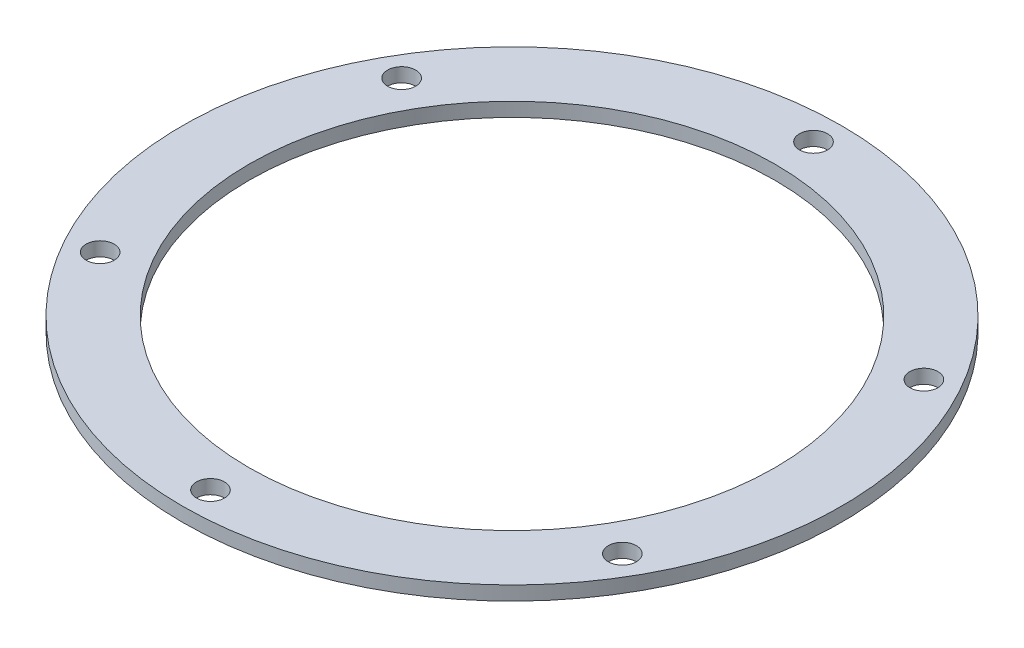
SolidWorks part; units mm, degrees
material "PLA"
ref_plane "Front Plane" through (0, 0, 0) normal (0, 0, 1) x (1, 0, 0)
ref_plane "Top Plane" through (0, 0, 0) normal (0, 1, 0) x (1, 0, 0)
ref_plane "Right Plane" through (0, 0, 0) normal (1, 0, 0) x (0, 0, -1)
sketch "Sketch1" plane through (0, 0, 0) normal (0, 1, 0) x (1, 0, 0)
  circle A0 centre (0, 0) radius 47
  circle A1 centre (0, 0) radius 37.5
  circle A2 centre (0, 0) radius 43 construction
  circle A3 centre (0, 43) radius 2
  circle A4 centre (37.2391, 21.5) radius 2
  circle A5 centre (37.2391, -21.5) radius 2
  circle A6 centre (0, -43) radius 2
  circle A7 centre (-37.2391, -21.5) radius 2
  circle A8 centre (-37.2391, 21.5) radius 2
  point P19 (0, 0)
  dimension "D1" = 94
  dimension "D2" = 75
  dimension "D3" = 86
  dimension "D4" = 4
  dimension "D5" = 6
extrude "Boss-Extrude1" add sketch "Sketch1" along normal blind 2
equation "\"Np_b\" = 39"
equation "\"Np_s\" = 33"
equation "\"Nr_b\" = 144"
equation "\"Nr_s\" = 138"
equation "\"Ns\" = 66"
equation "\"Motor_case_ID\" = 82.0"
equation "\"Motor_case_OD_base_to_chamfer\" = 5"
equation "\"Motor_case_OD_max\" = 96.5"
equation "\"Motor_case_thickness\" = 2.5"
equation "\"air_flow_hole_offset\" = 3"
equation "\"standard_bearing_insertion_chamfer\" = 0.5"
equation "\"alpha_p_b\" = 0.8539582918412414"
equation "\"alpha_p_s\" = 0.8539582918412449"
equation "\"alpha_r_b\" = 0.8539582918412343"
equation "\"alpha_r_s\" = 0.8539582918412485"
equation "\"alpha_s\" = 0.8539582918412449"
equation "\"base_plate_thickness\" = 4"
equation "\"bearing_ID\" = 60"
equation "\"bearing_OD\" = 78"
equation "\"bearing_height\" = 10"
equation "\"bearing mount thickness\" = 8"
equation "\"bearing_retainer_thickness\" = 2"
equation "\"beta_p_b\" = 2.907468031702132"
equation "\"beta_p_s\" = 3.7466288708629643"
equation "\"beta_r_b\" = 2.9579165836824686"
equation "\"beta_r_s\" = 3.0122644097694535"
equation "\"beta_s\" = 1.0193561435902372"
equation "\"carrier_PCD\" = 52.5"
equation "\"carrier_bearing_step_width\" = 1.5"
equation "\"carrier_small_ring_inner_bearing_ID\" = 20"
equation "\"carrier_small_ring_inner_bearing_OD\" = 32"
equation "\"carrier_small_ring_inner_bearing_flap\" = 2"
equation "\"carrier_small_ring_inner_bearing_height\" = 7"
equation "\"carrier_thickness\" = 4"
equation "\"carrier_trapezoidal_support_hole_PCD_offset_bearing_ID\" = 4"
equation "\"carrier_trapezoidal_support_hole_dia\" = 3"
equation "\"carrier_trapezoidal_support_hole_socket_head_dia\" = 5.5"
equation "\"carrier_trapezoidal_support_hole_wrench_size\" = 5.5"
equation "\"carrier_trapezoidal_support_sun_offset\" = 5"
equation "\"case_dist\" = 6.5"
equation "\"case_mounting_PCD\" = 89.0"
equation "\"case_mounting_bolt_depth\" = 4.5"
equation "\"case_mounting_hole_allen_socket_dia\" = 5.5"
equation "\"case_mounting_hole_dia\" = 3"
equation "\"case_mounting_hole_shift\" = 1.0"
equation "\"case_mounting_nut_clearance\" = 2"
equation "\"case_mounting_nut_thickness\" = 2.4"
equation "\"case_mounting_surface_height\" = 4"
equation "\"case_mounting_wrench_size\" = 5.5"
equation "\"central_hole_offset_from_motor_mount_PCD\" = 5"
equation "\"clearance_case_mount_holes_shell_thickness\" = 1"
equation "\"clearance_motor_and_case\" = 5.0"
equation "\"clearance_planet\" = 1.5"
equation "\"clearance_sun_coupler_sec_carrier\" = 1.5"
equation "\"clr_tip_root\" = 0.125"
equation "\"clr_tip_root_s\" = 0.125"
equation "\"db_p_b\" = 18.324006105325214"
equation "\"db_p_s\" = 15.50492824296749"
equation "\"db_r_b\" = 67.65786869658541"
equation "\"db_r_s\" = 64.83879083422768"
equation "\"db_s\" = 31.00985648593498"
equation "\"dp_p_b\" = 19.5"
equation "\"dp_p_s\" = 16.5"
equation "\"dp_r_b\" = 72.0"
equation "\"dp_r_s\" = 69.0"
equation "\"dp_s\" = 33.0"
equation "\"driver_lower_holes_dist_from_center\" = 13"
equation "\"driver_mount_height\" = 6"
equation "\"driver_mount_holes_dia\" = 3"
equation "\"driver_mount_inserts_OD\" = 4.8"
equation "\"driver_mount_thickness\" = 1.5"
equation "\"driver_side_holes_dist_from_center\" = 22.5"
equation "\"driver_upper_holes_dist_from_center\" = 29"
equation "\"fw_p_b\" = 18.602610884769575"
equation "\"fw_p_s\" = 22.55792585723615"
equation "\"fw_r_b\" = 18.602610884769575"
equation "\"fw_r_s\" = 21.05792585723615"
equation "\"fw_s_calc\" = 1.5726146484026726"
equation "\"fw_s_used\" = 48.660536742005725"
equation "\"gear_casing_big_ring_to_bearing_dist\" = 31.55792585723615"
equation "\"gear_casing_thickness\" = 4"
equation "\"h_a\" = 0.5"
equation "\"h_b\" = 0.625"
equation "\"h_f\" = 0.625"
equation "\"module\" = 0.5"
equation "\"motor_OD\" = 72"
equation "\"motor_case_OD_base\" = 87.0"
equation "\"motor_height\" = 27"
equation "\"motor_mount_hole_PCD\" = 32"
equation "\"motor_mount_hole_dia\" = 4"
equation "\"motor_mount_hole_num\" = 4"
equation "\"motor_output_hole_CSK_OD\" = 6"
equation "\"motor_output_hole_CSK_head_height\" = 1.5"
equation "\"motor_output_hole_PCD\" = 22"
equation "\"motor_output_hole_dia\" = 3"
equation "\"motor_output_hole_num\" = 4"
equation "\"num_planet\" = 6"
equation "\"output_mounting_PCD\" = 86"
equation "\"output_mounting_hole_dia\" = 4"
equation "\"output_mounting_nut_depth\" = 3"
equation "\"output_mounting_nut_thickness\" = 3.2"
equation "\"output_mounting_nut_wrench_size\" = 7"
equation "\"pattern_bulge_dia\" = 3"
equation "\"pattern_depth\" = 2"
equation "\"pattern_num_bulge\" = 18"
equation "\"pattern_offset_from_motor_case_OD_base\" = 3"
equation "\"planet_bearing_OD\" = 12"
equation "\"planet_bearing_width\" = 3.5"
equation "\"planet_bore\" = 10"
equation "\"planet_pin_bolt_dia\" = 5"
equation "\"planet_pin_bolt_wrench_size\" = 8"
equation "\"planet_pin_socket_head_dia\" = 8.5"
equation "\"planet_shaft_dia\" = 8"
equation "\"planet_shaft_step_offset\" = 1"
equation "\"pressure_angle\" = 20.0"
equation "\"pressure angle\" = 20.0"
equation "\"ring_OD_b\" = 82.0"
equation "\"ring_radial_thickness\" = 5"
equation "\"ring_to_chamfer_clearance\" = 1.5"
equation "\"sec_carrier_thickness\" = 5"
equation "\"small_ring_case_thickness\" = 4"
equation "\"small_ring_output_wall_thickness\" = 5"
equation "\"small_ring_output_wall_to_bearing_shaft_attachement_hole_CSK_OD\" = 8"
equation "\"small_ring_output_wall_to_bearing_shaft_attachement_hole_CSK_head_height\" = 2.0"
equation "\"small_ring_output_wall_to_bearing_shaft_attachement_hole_depth\" = 6.5"
equation "\"small_ring_output_wall_to_bearing_shaft_attachement_hole_dia\" = 4"
equation "\"small_ring_output_wall_to_bearing_shaft_attachement_hole_num\" = 3"
equation "\"small_ring_output_wall_to_bearing_shaft_attachement_hole_pcd\" = 12"
equation "\"small_ring_output_wall_to_bearing_shaft_attachement_nut_thickness\" = 3.2"
equation "\"small_ring_output_wall_to_bearing_shaft_attachement_nut_wrench\" = 7"
equation "\"standard_clearance_1_5mm\" = 1.5"
equation "\"standard_fillet_1_5mm\" = 1.5"
equation "\"sun_central_bolt_dia\" = 5"
equation "\"sun_central_bolt_socket_head_dia\" = 8.5"
equation "\"sun_coupler_hub_thickness\" = 4"
equation "\"sun_hub_dia\" = 28.0"
equation "\"sun_shaft_bearing_ID\" = 8"
equation "\"sun_shaft_bearing_OD\" = 16"
equation "\"sun_shaft_bearing_width\" = 5"
equation "\"wire_slot_dist_from_center\" = 26"
equation "\"wire_slot_length\" = 10"
equation "\"wire_slot_radius\" = 2.5"
equation "\"tight_clearance_3DP\" = 0.4"
equation "\"loose_clearance_3DP\" = 0.8"
equation "\"D1@Sketch1\"= \"bearing_OD\" + \"bearing mount thickness\" * 2"
equation "\"D2@Sketch1\"=\"bearing_OD\" -  \"standard_clearance_1_5mm\"*2"
equation "\"D3@Sketch1\"= \"output_mounting_PCD\""
equation "\"D4@Sketch1\"= \"output_mounting_hole_dia\""
equation "\"D1@Boss-Extrude1\"= \"bearing_retainer_thickness\""
